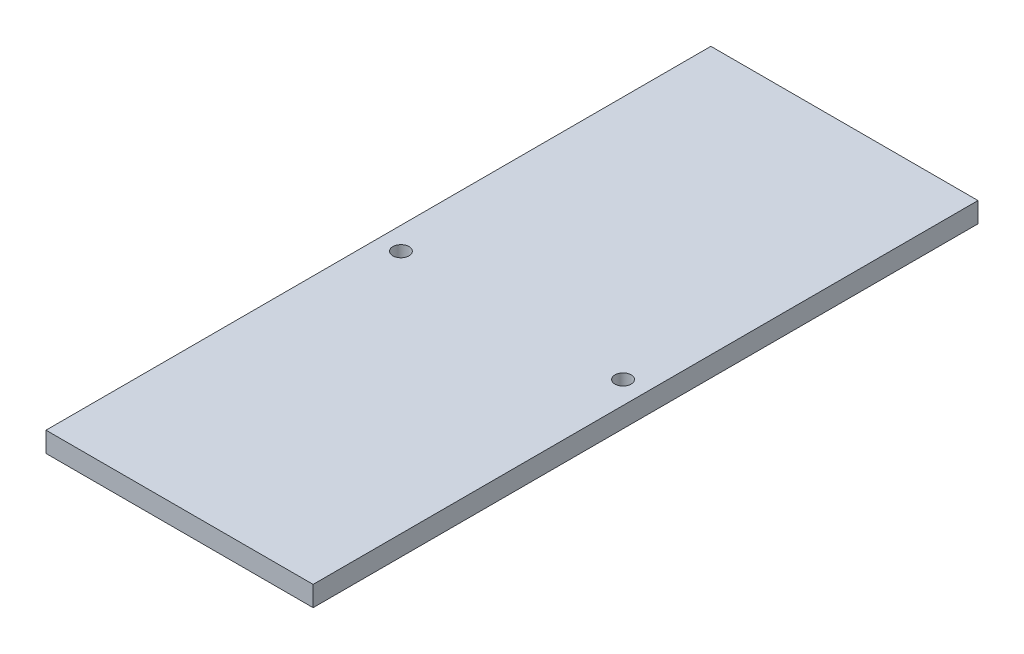
SolidWorks part; units mm, degrees
ref_plane "Front Plane" through (0, 0, 0) normal (0, 0, 1) x (1, 0, 0)
ref_plane "Top Plane" through (0, 0, 0) normal (0, 1, 0) x (1, 0, 0)
ref_plane "Right Plane" through (0, 0, 0) normal (1, 0, 0) x (0, 0, -1)
sketch "Sketch1" plane through (0, 0, 0) normal (0, 1, 0) x (1, 0, 0)
  line L0 (-13.97, 0) -> (13.97, 0) construction
  line L1 (-16.8, -41.8151) -> (16.8, -41.8151)
  line L2 (-16.8, -41.8151) -> (-16.8, 41.8151)
  line L3 (-16.8, 41.8151) -> (16.8, 41.8151)
  line L4 (16.8, -41.8151) -> (16.8, 41.8151)
  line L5 (-16.8, -41.8151) -> (16.8, 41.8151) construction
  line L6 (-16.8, 41.8151) -> (16.8, -41.8151) construction
  circle A0 centre (-13.97, 0) radius 1.016
  circle A1 centre (13.97, 0) radius 1.016
  point P0 (0, 0)
  point P10 (0, 0)
  point P11 (0, 0)
  dimension "D1" = 27.94
extrude "Boss-Extrude1" add sketch "Sketch1" along normal blind 2.54
